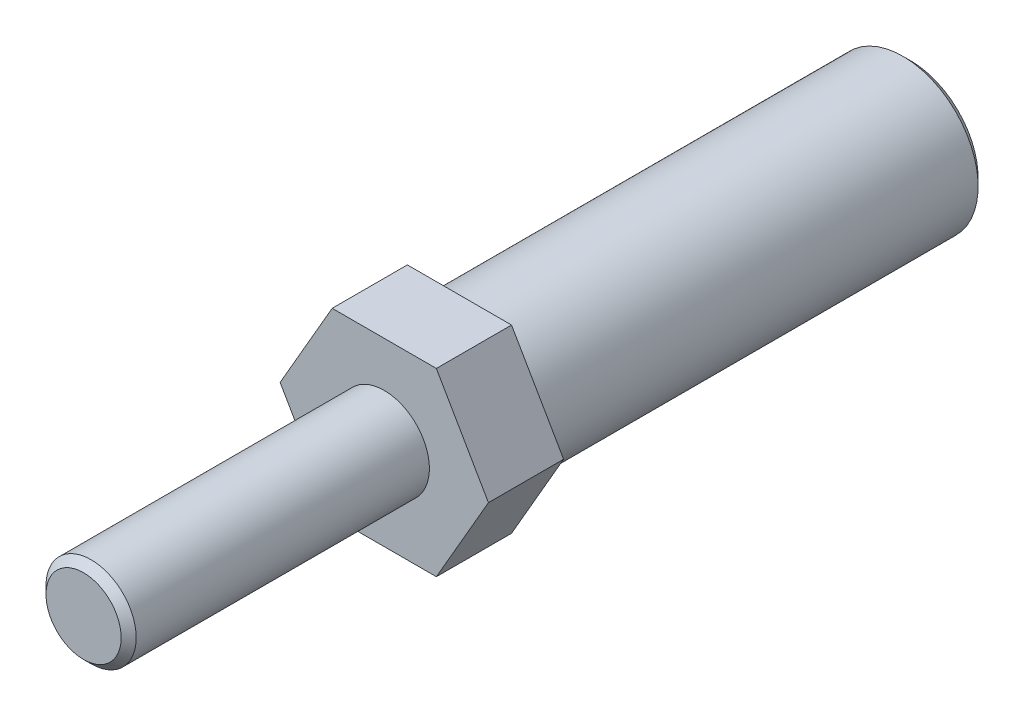
SolidWorks part; units mm, degrees
ref_plane "Plano frontal" through (0, 0, 0) normal (0, 0, 1) x (1, 0, 0)
ref_plane "Plano superior" through (0, 0, 0) normal (0, 1, 0) x (1, 0, 0)
ref_plane "Plano direito" through (0, 0, 0) normal (1, 0, 0) x (0, 0, -1)
sketch "Esboço1" plane through (0, 0, 0) normal (0, 0, 1) x (1, 0, 0)
  line L1 (6.9282, 0) -> (3.4641, 6)
  line L2 (3.4641, 6) -> (-3.4641, 6)
  line L3 (-3.4641, 6) -> (-6.9282, 0)
  line L4 (-6.9282, 0) -> (-3.4641, -6)
  line L5 (-3.4641, -6) -> (3.4641, -6)
  line L6 (3.4641, -6) -> (6.9282, 0)
  circle A0 centre (0, 0) radius 6 construction
  dimension "D1" = 12
extrude "Extrusão1" add sketch "Esboço1" along normal mid plane 5
sketch "Esboço2" plane through (0, 0, 2.5) normal (0, 0, 1) x (1, 0, 0)
  circle A0 centre (0, 0) radius 3
  dimension "D1" = 6
extrude "Extrusão2" add sketch "Esboço2" along normal blind 20
sketch "Esboço3" plane through (0, 0, -2.5) normal (0, 0, -1) x (-1, 0, 0)
  circle A0 centre (0, 0) radius 5
  dimension "D1" = 10
extrude "Extrusão3" add sketch "Esboço3" along normal blind 30
chamfer "Chanfro1" distance 0.5 angle 45 2 edges at (-5, 0, -32.5) (3, 0, 22.5)
